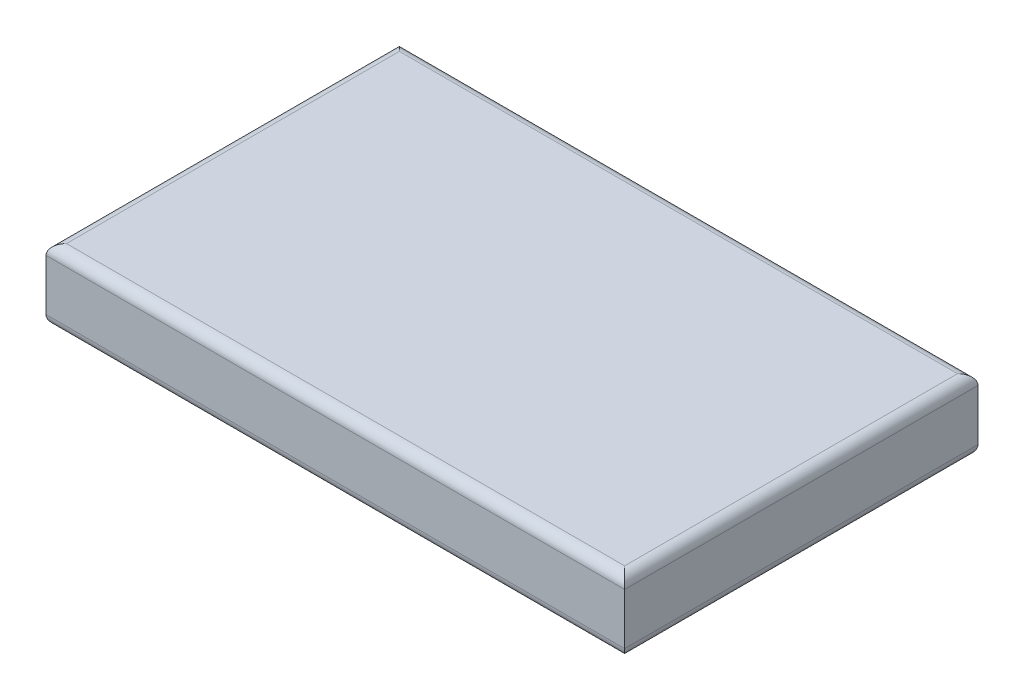
SolidWorks part; units mm, degrees
material "Lipo"
ref_plane "前基準面" through (0, 0, 0) normal (0, 0, 1) x (1, 0, 0)
ref_plane "上基準面" through (0, 0, 0) normal (0, 1, 0) x (1, 0, 0)
ref_plane "右基準面" through (0, 0, 0) normal (1, 0, 0) x (0, 0, -1)
sketch "草圖1" plane through (0, 0, 0) normal (0, 1, 0) x (1, 0, 0)
  line L1 (0, 0) -> (56.5, 0)
  line L2 (0, 0) -> (0, 34.5)
  line L3 (0, 34.5) -> (56.5, 34.5)
  line L4 (56.5, 0) -> (56.5, 34.5)
  dimension "D1" = 34.5
  dimension "D2" = 56.5
extrude "填料-伸長1" add sketch "草圖1" along normal blind 7
fillet "圓角1" radius 1 8 edges at (0, 7, -17.25) (0, 0, -17.25) (28.25, 7, -34.5) (28.25, 0, -34.5) (56.5, 0, -17.25) (56.5, 7, -17.25) (28.25, 0, 0) (28.25, 7, 0)
